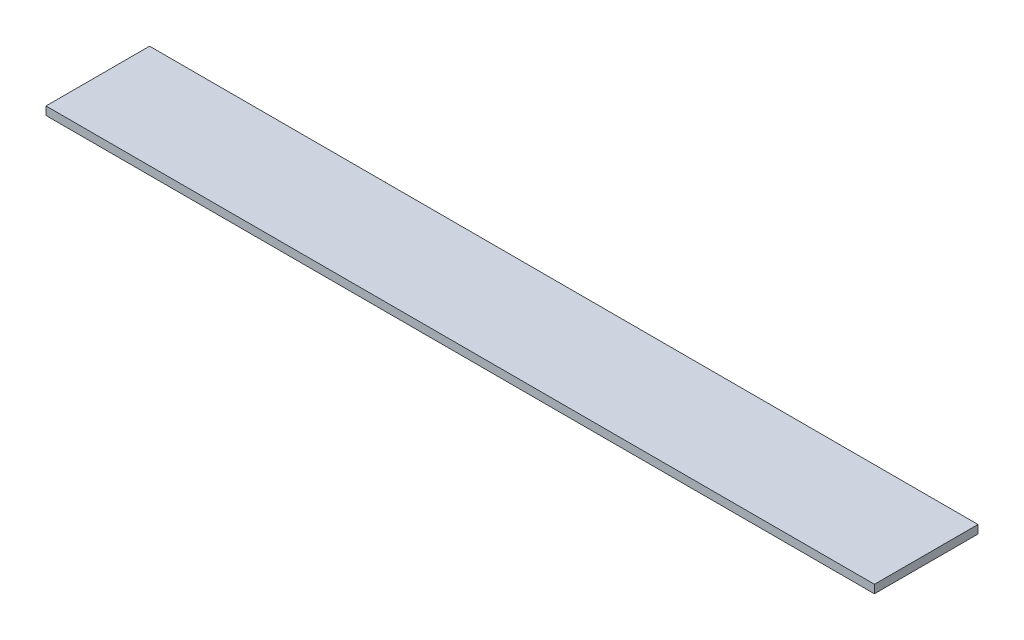
SolidWorks part; units mm, degrees
ref_plane "Front Plane" through (0, 0, 0) normal (0, 0, 1) x (1, 0, 0)
ref_plane "Top Plane" through (0, 0, 0) normal (0, 1, 0) x (1, 0, 0)
ref_plane "Right Plane" through (0, 0, 0) normal (1, 0, 0) x (0, 0, -1)
sketch "Sketch1" plane through (0, 0, 0) normal (0, 1, 0) x (1, 0, 0)
  line L1 (-100, 12.5) -> (100, 12.5)
  line L2 (-100, 12.5) -> (-100, -12.5)
  line L3 (-100, -12.5) -> (100, -12.5)
  line L4 (100, 12.5) -> (100, -12.5)
  line L5 (-100, 12.5) -> (100, -12.5) construction
  line L6 (-100, -12.5) -> (100, 12.5) construction
  point P0 (0, 0)
  dimension "D1" = 25
  dimension "D2" = 200
extrude "Boss-Extrude1" add sketch "Sketch1" along normal blind 2
